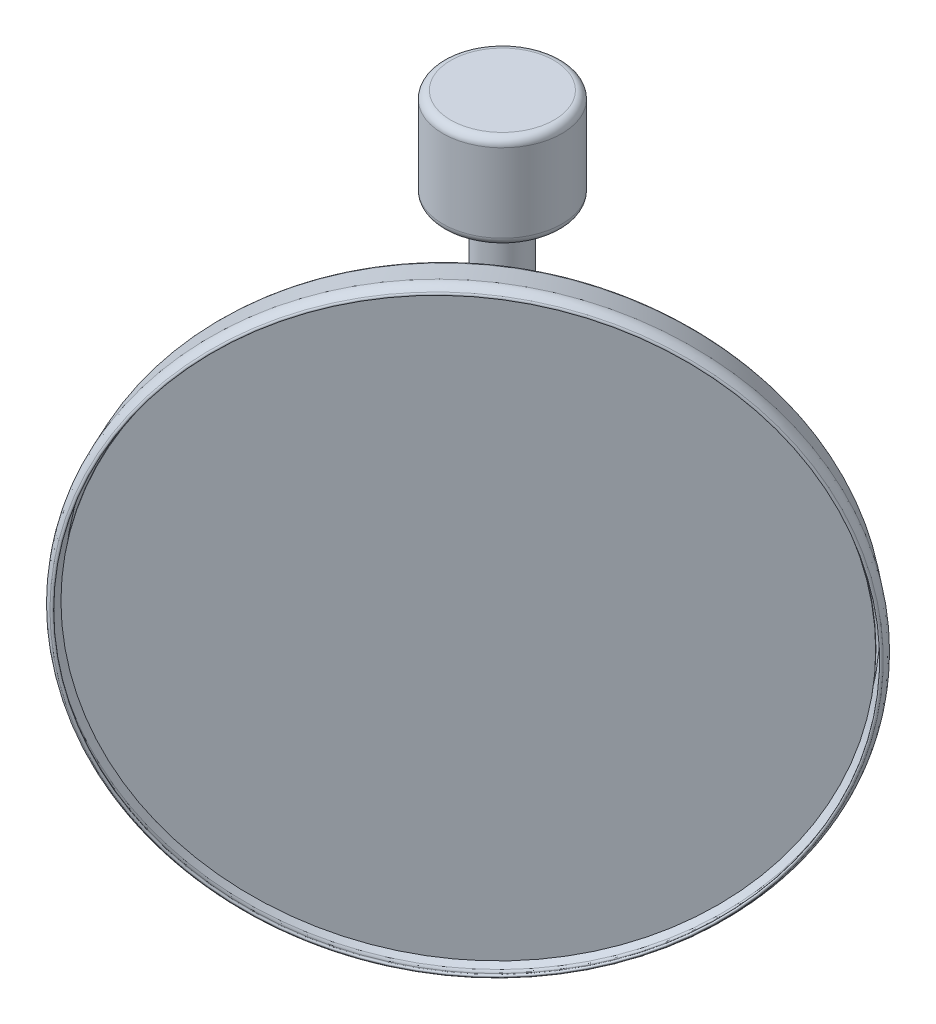
SolidWorks part; units mm, degrees
ref_plane "Front Plane" through (0, 0, 0) normal (0, 0, 1) x (1, 0, 0)
ref_plane "Top Plane" through (0, 0, 0) normal (0, 1, 0) x (1, 0, 0)
ref_plane "Right Plane" through (0, 0, 0) normal (1, 0, 0) x (0, 0, -1)
sketch "Sketch1" plane through (0, 0, 0) normal (0, 1, 0) x (1, 0, 0)
  line L0 (-7.7678, -6.2978) -> (-70.4437, -57.1129)
  line L1 (-7.9148, -7.7043) -> (-69.7661, -57.8508)
  line L2 (-7.9148, -7.7043) -> (-7.138, -7.0746)
  line L3 (-7.7678, -6.2978) -> (-7.138, -7.0746)
  line L4 (-70.3003, -60.1275) -> (-66.0908, -68.7581)
  line L5 (-7.7678, -6.2978) -> (1.7952, -18.0928) construction
  line L8 (-71.2373, -60.4876) -> (-66.9634, -69.2503)
  line L13 (0, 0) -> (32.8039, -40.4607) construction
  line L14 (-64.1463, -70.2681) -> (0.3886, -17.9458) construction
  line L15 (-63.9112, -71.3648) -> (1.7952, -18.0928) construction
  line L16 (-7.9148, -7.7043) -> (0.3886, -17.9458) construction
  spline S0 degree 2 poles (-70.4437, -57.1129) (-71.8226, -58.5234) (-71.2373, -60.4876) knots 0 0 0 1 1 1
  spline S1 degree 2 poles (-66.9634, -69.2503) (-65.8825, -70.9451) (-63.9112, -71.3648) knots 0 0 0 1 1 1
  spline S2 degree 1 poles (-69.7661, -57.8508) (-70.3003, -60.1275) knots 0 0 1 1 construction
  spline S3 degree 1 poles (-66.0908, -68.7581) (-64.1463, -70.2681) knots 0 0 1 1 construction
  spline S4 degree 3 poles (-69.7661, -57.8508) (-69.8436, -57.9328) (-69.995, -58.112) (-70.2135, -58.4504) (-70.3807, -58.8752) (-70.4267, -59.3434) (-70.386, -59.7673) (-70.3322, -60.0117) (-70.3003, -60.1275) knots 0.017932 0.017932 0.017932 0.017932 0.137683 0.257433 0.496934 0.736435 0.856186 0.975936 0.975936 0.975936 0.975936
  spline S5 degree 3 poles (-66.0908, -68.7581) (-65.9708, -68.9416) (-65.6948, -69.3001) (-65.2465, -69.7109) (-64.7427, -70.0368) (-64.3461, -70.2029) (-64.1463, -70.2681) knots 0.016474 0.016474 0.016474 0.016474 0.22661 0.436746 0.646882 0.857018 0.857018 0.857018 0.857018
  spline S6 degree 3 poles (-64.1463, -70.2681) (-62.4529, -70.9204) (-63.3757, -71.5365) (-63.9112, -71.3648) knots 0 0 0 0 1 1 1 1
  dimension "D1" = 1
revolve "Revolve2" add sketch "Sketch1" angle 360 about L13
sketch "Sketch2" plane through (0, 0, 0) normal (0, 1, 0) x (1, 0, 0)
  line L0 (0, 0) -> (32.8039, -40.4607) construction
  line L1 (0, 0) -> (32.8039, -40.4607) construction
  line L2 (0, 0) -> (-12.5956, 15.5355) construction
  point P2 (1.9469, 54.7944)
  dimension "D1" = 20
sketch "Sketch3" plane through (0, 0, 0) normal (0, 1, 0) x (1, 0, 0)
  point P0 (-12.5956, 15.5355)
sketch "Sketch4" plane through (0, 0, 0) normal (-0.6298, 0, -0.7768) x (-0.7768, 0, 0.6298)
  circle A1 centre (0, 0) radius 90.6874
  circle A2 centre (0, 0) radius 90.6874
  dimension "D1" = 0
ref_plane "Plane1" through (6.9276, 0, 8.5445) normal (0.6298, 0, 0.7768) x (0.7768, 0, -0.6298)
sketch "Sketch5" plane through (6.9276, 0, 8.5445) normal (0.6298, 0, 0.7768) x (0.7768, 0, -0.6298)
  circle A0 centre (0, 0) radius 92.4745 construction
  circle A1 centre (0, 0) radius 92.4745
extrude "Boss-Extrude1" add sketch "Sketch5" along normal blind 0.5 separate body
sketch "Sketch6" plane through (0, 0, 0) normal (0, 1, 0) x (1, 0, 0)
  line L0 (70.4437, 57.1129) -> (-70.4437, -57.1129) construction
  line L1 (70.4437, 57.1129) -> (0, 0)
  line L2 (0, 0) -> (-12.5956, 15.5355) construction
  line L3 (0, 0) -> (-12.5956, 15.5355)
  spline S0 degree 3 poles (-12.5956, 15.5355) (10.8857, 34.5731) (57.1433, 63.7037) (70.4437, 57.1129) knots 0.5 0.5 0.5 0.5 1 1 1 1
revolve "Revolve3" add sketch "Sketch6" angle 360 about L3
sketch "Sketch8" plane through (0, 0, 0) normal (0, 1, 0) x (1, 0, 0)
  line L1 (-15.885, 22.5139) -> (-11.1616, 16.688)
  line L2 (-12.5956, 15.5355) -> (-18.8933, 23.3033) construction
  line L3 (-15.885, 22.5139) -> (-2.6779, 33.2216)
  line L4 (-1.2713, 33.0746) -> (3.2847, 27.4552)
  arc A0 (-2.6779, 33.2216) -> (-1.2713, 33.0746) centre (-2.0481, 32.4449) cw
  spline S0 degree 3 poles (-1319.5895, -1378.8872) (1855.1975, 1616.1431) (-1916.3875, -1446.7626) (1628.9159, 1157.1259) knots -0.750334 -0.750334 -0.750334 -0.750334 2.424132 2.424132 2.424132 2.424132 only from (70.4437, 57.1129) to (-12.5956, 15.5355) construction
  spline S1 degree 3 poles (3.2847, 27.4552) (-1.9933, 23.749) (-6.9075, 20.0787) (-11.1616, 16.688) knots 0.902727 0.902727 0.902727 0.902727 0.990013 0.990013 0.990013 0.990013
  point P7 (-1.9011, 33.8514)
  dimension "D3" = 1
  dimension "D1" = 10
  dimension "D2" = 20
  dimension "D4" = 7.5
revolve "Revolve4" add sketch "Sketch8" angle 360 about L2
sketch "Sketch9" plane through (-17.314, 0, -21.3553) normal (-0.6298, 0, -0.7768) x (-0.7768, 0, 0.6298)
  circle A0 centre (0, 0) radius 8.5955
extrude "Boss-Extrude2" add sketch "Sketch9" along normal blind 5
sketch "Sketch10" plane through (-20.4629, 0, -25.2392) normal (-0.6298, 0, -0.7768) x (-0.7768, 0, 0.6298)
  circle A0 centre (0, 0) radius 14.0274
extrude "Boss-Extrude3" add sketch "Sketch10" along normal blind 30
sketch "Sketch11" plane through (0, 0, 0) normal (0, 1, 0) x (1, 0, 0)
  line L0 (-28.46, 57.3766) -> (-50.2524, 39.7083) construction
  circle A0 centre (-39.3562, 48.5424) radius 19
  dimension "D1" = 38
extrude "Boss-Extrude4" add sketch "Sketch11" along normal mid plane 50
fillet "Fillet1" radius 2.5 1 edges at (-42.168, 0.51, -29.7516)
fillet "Fillet2" radius 1 1 edges at (-31.359, 0, -16.405)
fillet "Fillet3" radius 2.5 1 edges at (-39.3562, -25, -29.5424)
sketch "Sketch12" plane through (0, 25, 0) normal (0, 1, 0) x (1, 0, 0)
  circle A0 centre (-39.3562, 48.5424) radius 7.5
  dimension "D1" = 15
extrude "Boss-Extrude5" add sketch "Sketch12" along normal blind 41
sketch "Sketch13" plane through (0, 66, 0) normal (0, 1, 0) x (1, 0, 0)
  circle A0 centre (-39.3562, 48.5424) radius 19
  dimension "D1" = 38
extrude "Boss-Extrude6" add sketch "Sketch13" along normal blind 30
fillet "Fillet4" radius 2.5 1 edges at (-39.3562, 96, -29.5424)
fillet "Fillet5" radius 2.5 4 edges at (-39.3562, 66, -41.0424) (-39.3562, 66, -29.5424) (-39.3562, 25, -41.0424) (-39.3562, 25, -29.5424)
